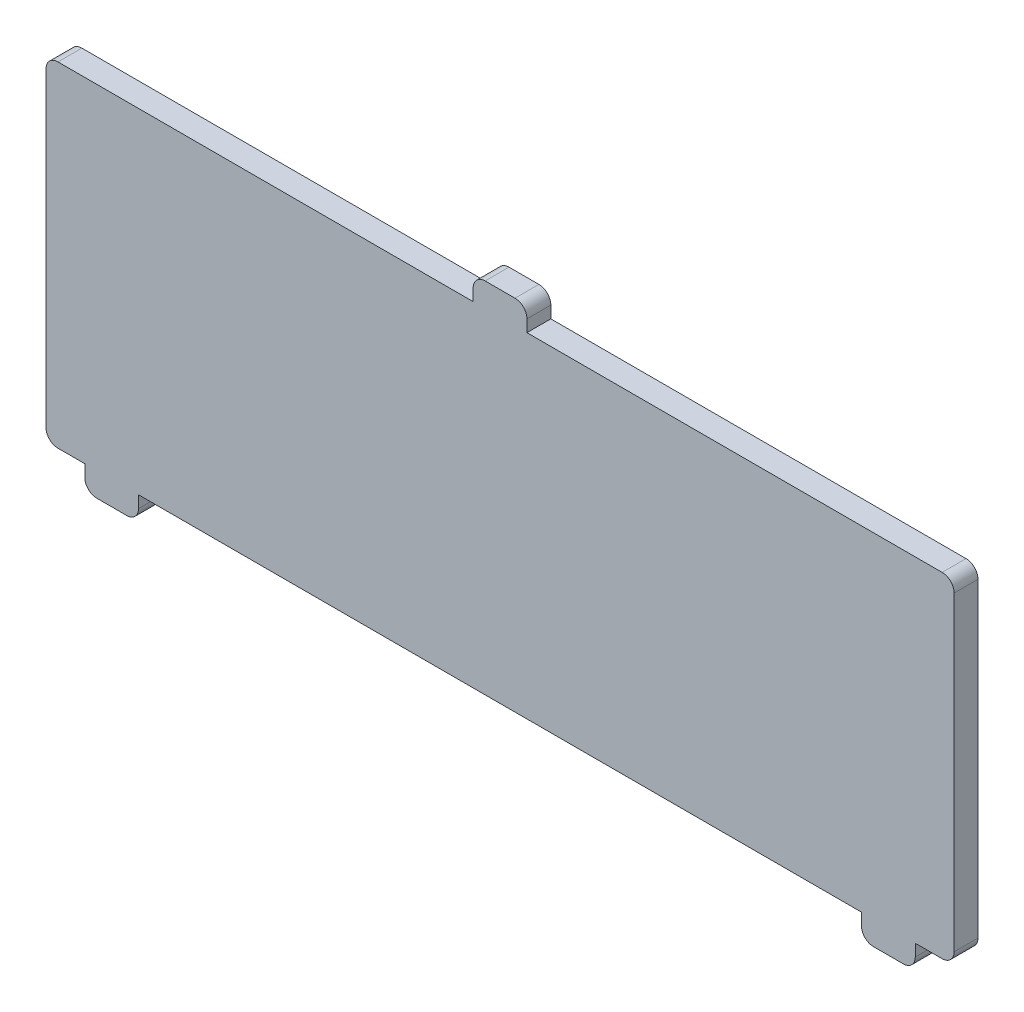
SolidWorks part; units mm, degrees
ref_plane "前基準面" through (0, 0, 0) normal (0, 0, 1) x (1, 0, 0)
ref_plane "上基準面" through (0, 0, 0) normal (0, 1, 0) x (1, 0, 0)
ref_plane "右基準面" through (0, 0, 0) normal (1, 0, 0) x (0, 0, -1)
sketch "Sketch1" plane through (0, 0, 0) normal (0, 0, 1) x (1, 0, 0)
  line L0 (0, 0) -> (0, 14) construction
  line L1 (-38, 14) -> (38, 14)
  line L2 (-38, 14) -> (-38, -14)
  line L3 (-38, -14) -> (38, -14)
  line L4 (38, 14) -> (38, -14)
  line L5 (-38, 14) -> (38, -14) construction
  line L6 (-38, -14) -> (38, 14) construction
  line L7 (0, 14) -> (0, -14) construction
  line L8 (-34.75, -14) -> (-30.25, -16) construction
  line L9 (-34.75, -14) -> (-30.25, -14)
  line L10 (-34.75, -14) -> (-34.75, -16)
  line L11 (-34.75, -16) -> (-30.25, -16)
  line L12 (-30.25, -14) -> (-30.25, -16)
  line L13 (-30.25, -14) -> (-29.5508, -16) construction
  line L14 (34.75, -16) -> (30.25, -16)
  line L15 (30.25, -14) -> (30.25, -16)
  line L16 (34.75, -14) -> (30.25, -14)
  line L17 (34.75, -14) -> (34.75, -16)
  line L18 (0, 0) -> (0, 22.3502) construction
  line L19 (-2.25, 16) -> (2.25, 14) construction
  line L20 (-2.25, 14) -> (2.25, 14)
  line L21 (-2.25, 14) -> (-2.25, 16)
  line L22 (-2.25, 16) -> (2.25, 16)
  line L23 (2.25, 14) -> (2.25, 16)
  line L24 (2.25, 16) -> (-2.25, 14) construction
  point P0 (0, 0)
  point P14 (-32.5, -15)
  point P24 (0, 15)
  dimension "D1" = 76
  dimension "D2" = 28
  dimension "D3" = 2
  dimension "D4" = 4.5
  dimension "D5" = 32.5
  dimension "D6" = 2
  dimension "D7" = 4.5
extrude "Boss-Extrude1" add sketch "Sketch1" along normal mid plane 2 contours L4 L1 L2 L3 | L12 L3 L10 L11 | L17 L3 L15 L14 | L23 L22 L21 L20
fillet "Fillet1" radius 1 10 edges at (38, -14, 0) (34.75, -16, 0) (30.25, -16, 0) (-30.25, -16, 0) (-34.75, -16, 0) (-38, -14, 0) (-38, 14, 0) (38, 14, 0) (2.25, 16, 0) (-2.25, 16, 0)
